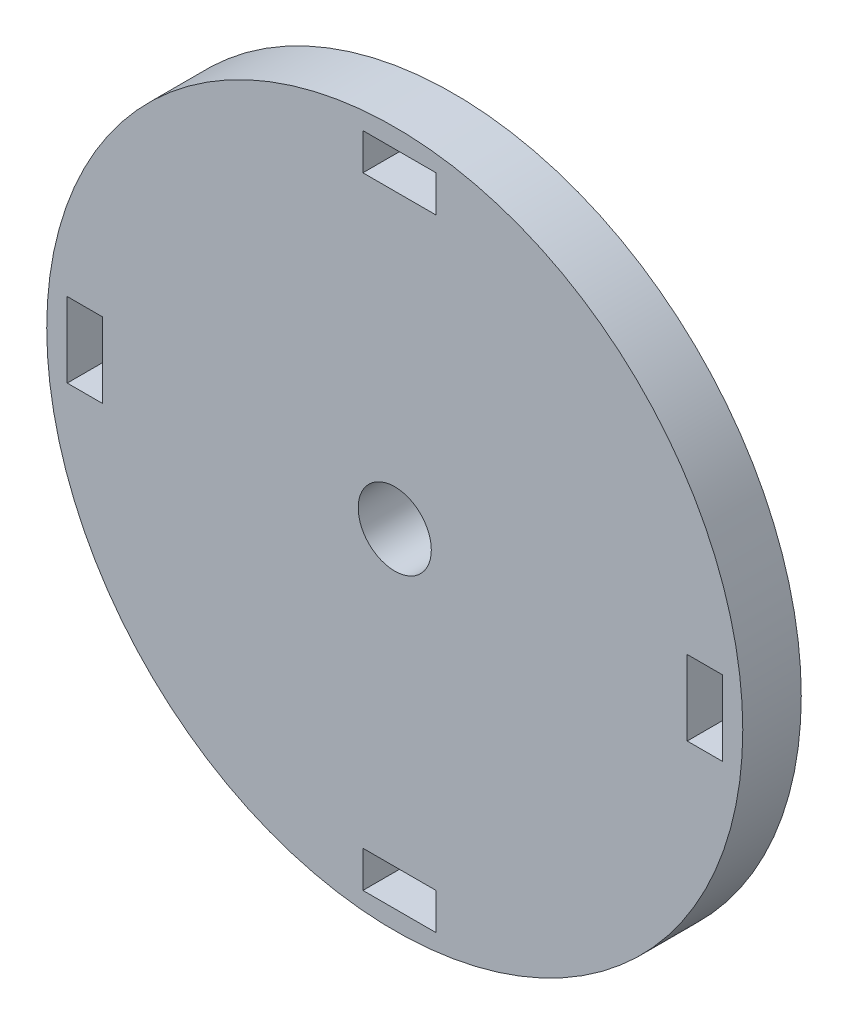
SolidWorks part; units mm, degrees
ref_plane "Front Plane" through (0, 0, 0) normal (0, 0, 1) x (1, 0, 0)
ref_plane "Top Plane" through (0, 0, 0) normal (0, 1, 0) x (1, 0, 0)
ref_plane "Right Plane" through (0, 0, 0) normal (1, 0, 0) x (0, 0, -1)
sketch "Sketch1" plane through (0, 0, 0) normal (0, 0, 1) x (1, 0, 0)
  circle A0 centre (0, 0) radius 11.9
extrude "Boss-Extrude1" add sketch "Sketch1" along normal blind 2
sketch "Sketch2" plane through (0, 0, 2) normal (0, 0, 1) x (1, 0, 0)
  line L0 (1.8803, 5.3031) -> (2.214, 4.9107)
  line L1 (-2.1775, 4.8815) -> (-1.71, 5.1758)
  arc A0 (1.8803, 5.3031) -> (-1.71, 5.1758) centre (0, 7.6407) cw
  arc A1 (2.214, 4.9107) -> (-2.1775, 4.8815) centre (0, 7.6407) cw
sketch "Sketch3" plane through (0, 0, 2) normal (0, 0, 1) x (1, 0, 0)
  line L0 (-11.9, 0) -> (11.9, 0) construction
  line L1 (11.9, 0) -> (-11.9, 0) construction
  line L2 (0, 0) -> (0, 11.9) construction
  line L3 (-10, 1.2818) -> (-11.1985, -1.2818) construction
  line L4 (10, -1.2818) -> (11.1985, -1.2818)
  line L5 (10, -1.2818) -> (10, 1.2818)
  line L6 (10, 1.2818) -> (11.1985, 1.2818)
  line L7 (11.1985, -1.2818) -> (11.1985, 1.2818)
  line L8 (10, -1.2818) -> (11.1985, 1.2818) construction
  line L9 (10, 1.2818) -> (11.1985, -1.2818) construction
  line L10 (-10, -1.2818) -> (-11.1985, 1.2818) construction
  line L11 (-11.1985, -1.2818) -> (-11.1985, 1.2818)
  line L12 (-10, 1.2818) -> (-11.1985, 1.2818)
  line L13 (-10, -1.2818) -> (-10, 1.2818)
  line L14 (-10, -1.2818) -> (-11.1985, -1.2818)
  circle A0 centre (0, 0) radius 11.9 construction
  point P7 (10.5993, 0)
  point P17 (-10.5993, 0)
  dimension "D1" = 10
extrude "Cut-Extrude1" cut sketch "Sketch3" against normal up to next
sketch "Sketch4" plane through (0, 0, 2) normal (0, 0, 1) x (1, 0, 0)
  circle A0 centre (0, 0) radius 1.25
extrude "Cut-Extrude2" cut sketch "Sketch4" against normal up to next
sketch "Sketch5" plane through (0, 0, 0) normal (0, 0, -1) x (-1, 0, 0)
  line L0 (0, 0) -> (7.8371, 0) construction
  line L1 (1.0886, -10) -> (-1.4114, -10)
  line L2 (1.0886, -10) -> (1.0886, -11.25)
  line L3 (1.0886, -11.25) -> (-1.4114, -11.25)
  line L4 (-1.4114, -10) -> (-1.4114, -11.25)
  line L5 (1.0886, -10) -> (-1.4114, -11.25) construction
  line L6 (1.0886, -11.25) -> (-1.4114, -10) construction
  line L7 (1.0886, 11.25) -> (-1.4114, 10) construction
  line L8 (1.0886, 10) -> (-1.4114, 11.25) construction
  line L9 (-1.4114, 10) -> (-1.4114, 11.25)
  line L10 (1.0886, 11.25) -> (-1.4114, 11.25)
  line L11 (1.0886, 10) -> (1.0886, 11.25)
  line L12 (1.0886, 10) -> (-1.4114, 10)
  point P0 (-0.1614, -10.625)
  point P12 (-0.1614, 10.625)
  dimension "D1" = 2.5
  dimension "D2" = 1.25
  dimension "D3" = 10
extrude "Cut-Extrude3" cut sketch "Sketch5" against normal up to next
